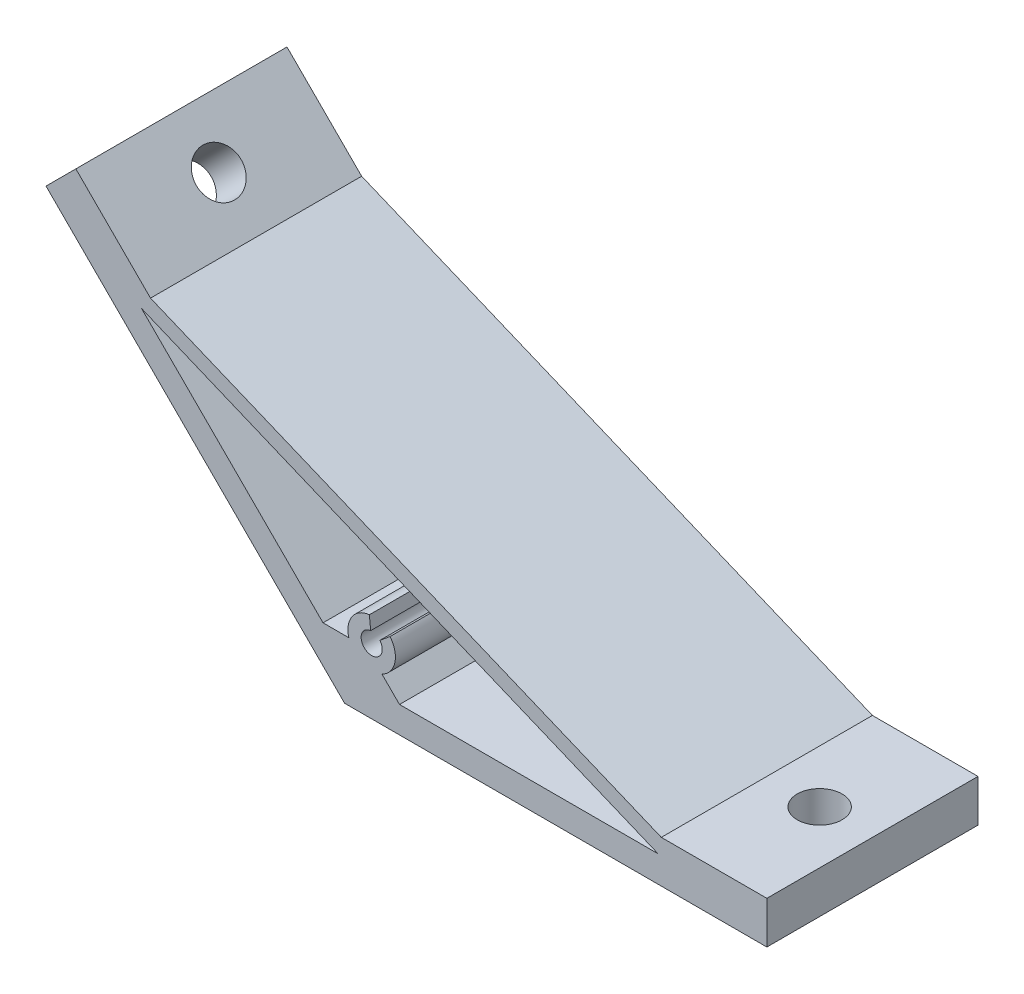
SolidWorks part; units mm, degrees
ref_plane "前视基准面" through (0, 0, 0) normal (0, 0, 1) x (1, 0, 0)
ref_plane "上视基准面" through (0, 0, 0) normal (0, 1, 0) x (1, 0, 0)
ref_plane "右视基准面" through (0, 0, 0) normal (1, 0, 0) x (0, 0, -1)
sketch "草图1" plane through (0, 0, 0) normal (0, 0, 1) x (1, 0, 0)
  line L0 (6992.6877, -1288.6549) -> (7072.6877, -1288.6549)
  line L1 (7003.0909, -1283.6549) -> (7052.0909, -1283.6549)
  line L2 (7052.6877, -1280.6549) -> (7072.6877, -1280.6549)
  line L3 (7003.0909, -1283.6549) -> (7029.4034, -1283.6549)
  line L4 (7072.6877, -1288.6549) -> (7072.6877, -1280.6549)
  line L5 (6997.6265, -1274.2736) -> (6997.3838, -1271.7854)
  line L6 (6999.3656, -1274.9939) -> (7001.2967, -1273.4062)
  line L7 (6992.6877, -1288.6549) -> (6936.1191, -1232.0864)
  line L8 (6988.6024, -1277.4986) -> (6954.2187, -1243.1149)
  line L9 (6955.9181, -1240.5717) -> (6941.776, -1226.4295)
  line L10 (6936.1191, -1232.0864) -> (6941.776, -1226.4295)
  line L11 (6955.9181, -1240.5717) -> (7052.6877, -1280.6549)
  line L12 (6954.2187, -1243.1149) -> (7052.0909, -1283.6549)
  line L13 (7052.0909, -1283.6549) -> (7009.0909, -1283.6549)
  line L14 (7003.0909, -1283.6549) -> (6999.7605, -1280.3246)
  line L15 (6988.6024, -1277.4986) -> (6993.4934, -1277.4986)
  arc A0 (6997.3838, -1271.7854) -> (6993.4934, -1277.4986) centre (6997.8207, -1276.2641) ccw
  arc A1 (6999.7605, -1280.3246) -> (7001.2967, -1273.4062) centre (6997.8207, -1276.2641) ccw
  arc A2 (6997.6265, -1274.2736) -> (6999.3656, -1274.9939) centre (6997.8207, -1276.2641) ccw
extrude "凸台-拉伸1" add sketch "草图1" along normal mid plane 40 contours L11 L9 L10 L7 L0 L4 L2 A2 L5 A0 L15 L8 L12 L1 L3 L14 A1 L6
hole_wizard "Ø8.5 (8.5) 直径孔1" positions "草图3" profile "草图2" hole size "Ø8.5" standard "GB" end condition through all
sketch "草图3" plane through (2852.0164, 2852.0164, 0) normal (-0.7071, -0.7071, 0) x (0.7071, -0.7071, 0)
  line L1 (5775.7935, 20) -> (5775.7935, -20) construction
  point P1 (5785.7935, 0)
  point P11 (5775.7935, 0)
  dimension "D1" = 10
sketch "草图2" plane through (6943.1902, -1239.1575, 0) normal (0, 0, 1) x (0.7071, -0.7071, 0)
  line L0 (0, 0) -> (0, 100.5685)
  line L1 (0, 100.5685) -> (4.25, 100.5685)
  line L2 (4.25, 100.5685) -> (4.25, 0)
  line L5 (4.25, 0) -> (0, 0)
  line L11 (0, -6.35) -> (0, 107.95) construction
  dimension "通孔孔直径" = 8.5
  dimension "通孔孔深度" = 100.5685
hole_wizard "Ø8.5 (8.5) 直径孔2" positions "草图5" profile "草图4" hole size "Ø8.5" standard "GB" end condition through all
sketch "草图5" plane through (0, -1288.6549, 0) normal (0, -1, 0) x (1, 0, 0)
  line L1 (7072.6877, 20) -> (7072.6877, -20) construction
  point P0 (7062.6877, 0)
  point P10 (7072.6877, 0)
  dimension "D2" = 10
sketch "草图4" plane through (7062.6877, -1288.6549, 0) normal (1, 0, 0) x (0, 0, -1)
  line L0 (0, 0) -> (0, 62.2254)
  line L1 (0, 62.2254) -> (4.25, 62.2254)
  line L2 (4.25, 62.2254) -> (4.25, 0)
  line L5 (4.25, 0) -> (0, 0)
  line L11 (0, -6.35) -> (0, 107.95) construction
  dimension "通孔孔直径" = 8.5
  dimension "通孔孔深度" = 62.2254
